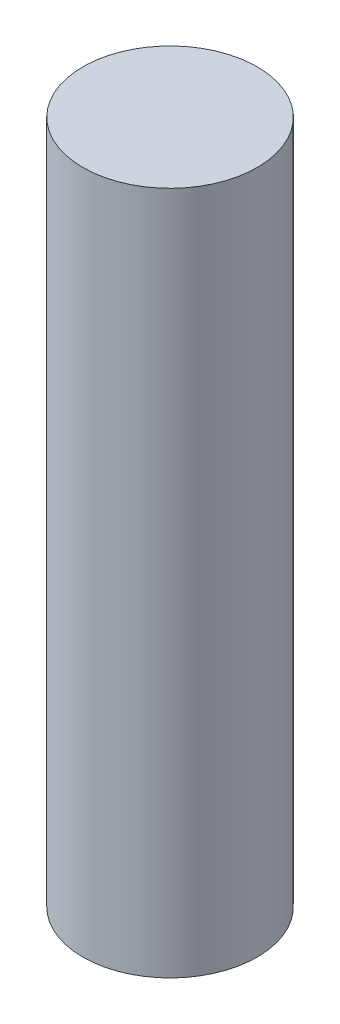
SolidWorks part; units mm, degrees
ref_plane "Front Plane" through (0, 0, 0) normal (0, 0, 1) x (1, 0, 0)
ref_plane "Top Plane" through (0, 0, 0) normal (0, 1, 0) x (1, 0, 0)
ref_plane "Right Plane" through (0, 0, 0) normal (1, 0, 0) x (0, 0, -1)
sketch "Sketch1" plane through (0, 0, 0) normal (0, 1, 0) x (1, 0, 0)
  circle A0 centre (0, 0) radius 12.75
extrude "Boss-Extrude1" add sketch "Sketch1" along normal blind 100
